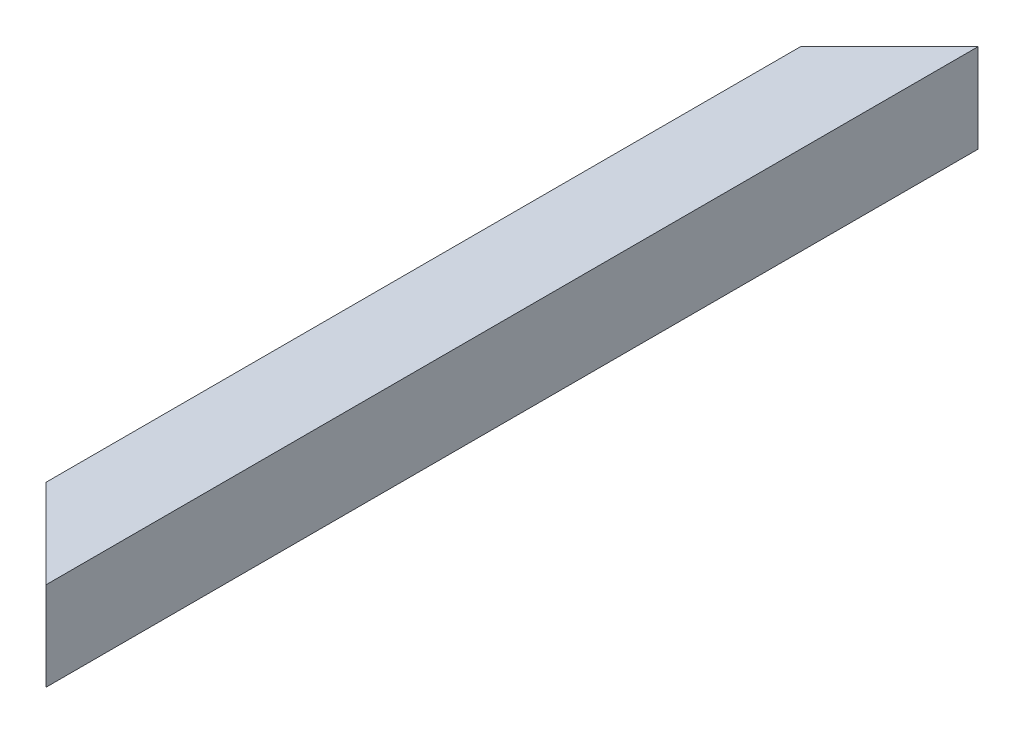
SolidWorks part; units mm, degrees
ref_plane "Front Plane" through (0, 0, 0) normal (0, 0, 1) x (1, 0, 0)
ref_plane "Top Plane" through (0, 0, 0) normal (0, 1, 0) x (1, 0, 0)
ref_plane "Right Plane" through (0, 0, 0) normal (1, 0, 0) x (0, 0, -1)
sketch "Sketch2" plane through (0, 0, 0) normal (0, 1, 0) x (1, 0, 0)
  line L1 (-225, 225) -> (225, 225) construction
  line L2 (-225, 225) -> (-225, -225) construction
  line L3 (-225, -225) -> (225, -225) construction
  line L4 (225, 225) -> (225, -225) construction
  point P4 (0, 225)
  point P5 (-225, 0)
  dimension "D1" = 450
sketch "Sketch3" plane through (0, 0, 0) normal (0, 0, 1) x (1, 0, 0)
  line L1 (-9.525, -9.525) -> (9.525, -9.525)
  line L2 (-9.525, -9.525) -> (-9.525, 9.525)
  line L3 (-9.525, 9.525) -> (9.525, 9.525)
  line L4 (9.525, -9.525) -> (9.525, 9.525)
  line L5 (-9.525, -9.525) -> (9.525, 9.525) construction
  line L6 (-9.525, 9.525) -> (9.525, -9.525) construction
  point P0 (0, 0)
  dimension "D1" = 19.05
extrude "Boss-Extrude1" add sketch "Sketch3" along normal mid plane 200
sketch "Sketch5" plane through (0, 0, -100) normal (0, 0, -1) x (-1, 0, 0)
  line L8 (-8.325, 8.325) -> (-8.325, -8.325)
  line L9 (-8.325, -8.325) -> (8.325, -8.325)
  line L10 (8.325, -8.325) -> (8.325, 8.325)
  line L11 (8.325, 8.325) -> (-8.325, 8.325)
  line L12 (-8.325, 8.325) -> (-8.325, -8.325)
  line L13 (-8.325, -8.325) -> (8.325, -8.325)
  line L14 (8.325, -8.325) -> (8.325, 8.325)
  line L15 (8.325, 8.325) -> (-8.325, 8.325)
  dimension "D1" = 1.2
extrude "Cut-Extrude1" cut sketch "Sketch5" against normal through all
sketch "Sketch7" plane through (0, 0, 0) normal (0, 1, 0) x (1, 0, 0)
  line L0 (9.525, 100) -> (-9.525, 100)
  line L1 (-9.525, 100) -> (-9.525, 80.95)
  line L2 (-9.525, -100) -> (-9.525, 100) construction
  line L3 (-9.525, 80.95) -> (9.525, 100)
  line L4 (-51.7279, 0) -> (51.7279, 0) construction
  line L5 (-9.525, -80.95) -> (9.525, -100)
  line L6 (-9.525, -100) -> (-9.525, -80.95)
  line L7 (9.525, -100) -> (-9.525, -100)
  point P10 (0, 0)
extrude "Cut-Extrude2" cut sketch "Sketch7" against normal through all both and the other way through all
